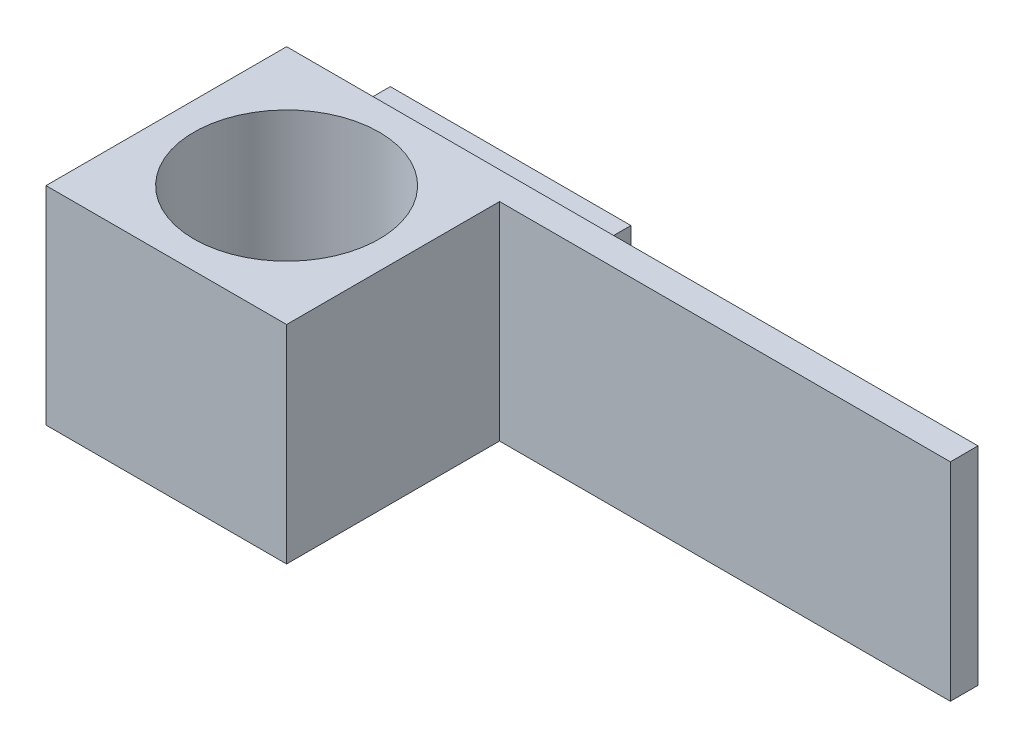
SolidWorks part; units mm, degrees
ref_plane "Front Plane" through (0, 0, 0) normal (0, 0, 1) x (1, 0, 0)
ref_plane "Top Plane" through (0, 0, 0) normal (0, 1, 0) x (1, 0, 0)
ref_plane "Right Plane" through (0, 0, 0) normal (1, 0, 0) x (0, 0, -1)
sketch "Sketch1" plane through (0, 0, 0) normal (0, 1, 0) x (1, 0, 0)
  line L1 (-17.4, 17.4) -> (17.4, 17.4)
  line L2 (-17.4, 17.4) -> (-17.4, -17.4)
  line L3 (-17.4, -17.4) -> (17.4, -17.4)
  line L4 (17.4, 13.4) -> (17.4, -17.4)
  line L5 (-17.4, 17.4) -> (17.4, -17.4) construction
  line L6 (-17.4, -17.4) -> (17.4, 17.4) construction
  line L11 (17.4, 17.4) -> (82.6, 17.4)
  line L13 (17.4, 13.4) -> (82.6, 13.4)
  line L14 (82.6, 17.4) -> (82.6, 13.4)
  circle A0 centre (0, 0) radius 13.4
  dimension "D1" = 26.8
  dimension "D2" = 34.8
  dimension "D3" = 34.8
extrude "Boss-Extrude1" add sketch "Sketch1" along normal blind 30 contours L14 L11 L4 L13 | L4 L1 L2 L3 A0
sketch "Sketch3" plane through (-17.4, 0, 0) normal (-1, 0, 0) x (0, 0, 1)
  line L0 (-17.4, 0) -> (-32.4, 0)
  line L1 (-32.4, 0) -> (-32.4, 3)
  line L2 (-32.4, 14.5) -> (-32.4, 17.5)
  line L3 (-32.4, 17.5) -> (-17.4, 17.5)
  line L4 (-17.4, 30) -> (-17.4, 0) construction
  line L5 (-17.4, 17.5) -> (-17.4, 10.5571)
  line L6 (-17.4, 7.5571) -> (-17.4, 0)
  line L7 (-24.8059, 7.5571) -> (-17.4, 7.5571)
  line L9 (-24.9647, 10.5571) -> (-17.4, 10.5571)
  arc A0 (-32.4, 3) -> (-24.8059, 7.5571) centre (-30.6861, 8.75) ccw
  arc A1 (-24.9647, 10.5571) -> (-32.4, 14.5) centre (-30.6861, 8.75) ccw
  dimension "D3" = 6
  dimension "D1" = 3
  dimension "D2" = 3
  dimension "D4" = 17.5
  dimension "D5" = 15
  dimension "D6" = 7.5571
extrude "Boss-Extrude2" add sketch "Sketch3" against normal blind 34.8
